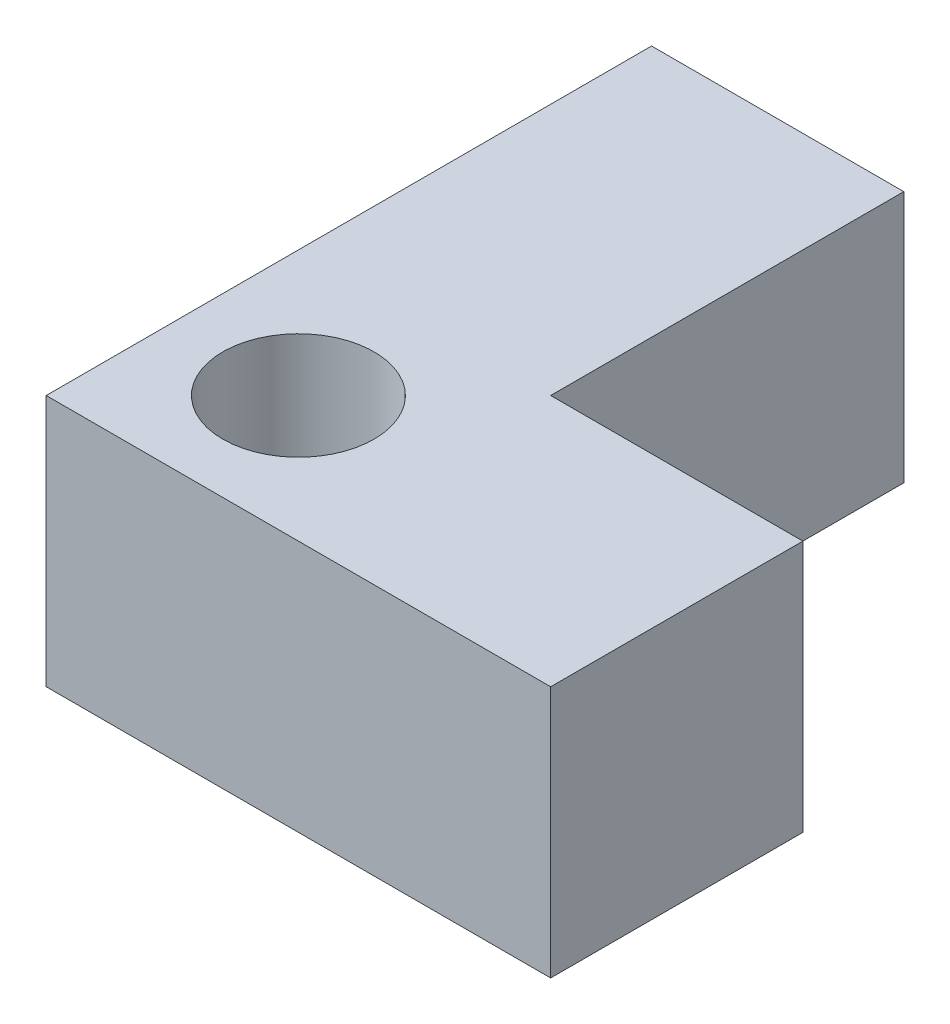
SolidWorks part; units mm, degrees
ref_plane "Front Plane" through (0, 0, 0) normal (0, 0, 1) x (1, 0, 0)
ref_plane "Top Plane" through (0, 0, 0) normal (0, 1, 0) x (1, 0, 0)
ref_plane "Right Plane" through (0, 0, 0) normal (1, 0, 0) x (0, 0, -1)
sketch "Sketch3" plane through (0, 0, 0) normal (0, 1, 0) x (1, 0, 0)
  line L0 (0, 0) -> (10, 0)
  line L1 (10, 0) -> (10, 5)
  line L2 (10, 5) -> (5, 5)
  line L3 (5, 5) -> (5, 12)
  line L4 (5, 12) -> (0, 12)
  line L5 (0, 12) -> (0, 0)
  dimension "D1" = 10
  dimension "D2" = 5
  dimension "D3" = 5
  dimension "D4" = 12
extrude "Boss-Extrude1" add sketch "Sketch3" along normal blind 5
sketch "Sketch4" plane through (0, 5, 0) normal (0, 1, 0) x (1, 0, 0)
  line L0 (0, 0) -> (10, 0) construction
  circle A0 centre (2.5, 2.5) radius 1.5
  point P5 (0, 0)
  dimension "D3" = 3
  dimension "D1" = 2.5
  dimension "D2" = 2.5
extrude "Cut-Extrude1" cut sketch "Sketch4" against normal through all
